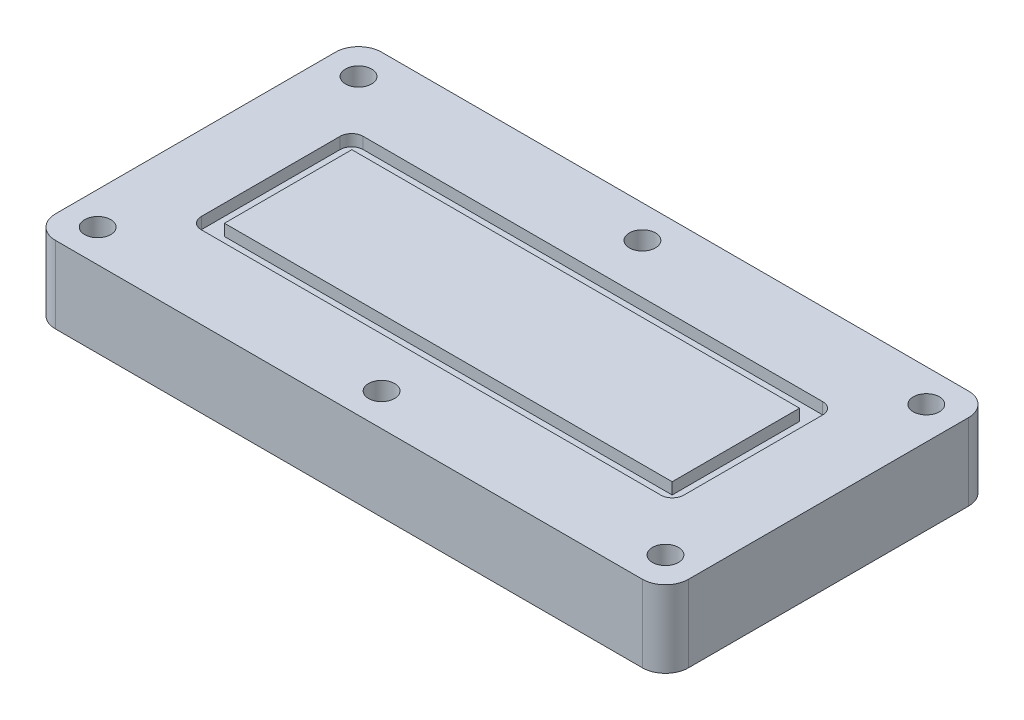
SolidWorks part; units mm, degrees
ref_plane "Front Plane" through (0, 0, 0) normal (0, 0, 1) x (1, 0, 0)
ref_plane "Top Plane" through (0, 0, 0) normal (0, 1, 0) x (1, 0, 0)
ref_plane "Right Plane" through (0, 0, 0) normal (1, 0, 0) x (0, 0, -1)
sketch "Sketch1" plane through (0, 0, 0) normal (0, 1, 0) x (1, 0, 0)
  line L1 (-52.3875, -26.9875) -> (52.3875, -26.9875)
  line L2 (-52.3875, -26.9875) -> (-52.3875, 26.9875)
  line L3 (-52.3875, 26.9875) -> (52.3875, 26.9875)
  line L4 (52.3875, -26.9875) -> (52.3875, 26.9875)
  line L5 (-52.3875, -26.9875) -> (52.3875, 26.9875) construction
  line L6 (-52.3875, 26.9875) -> (52.3875, -26.9875) construction
  point P0 (0, 0)
  dimension "D1" = 104.775
  dimension "D2" = 53.975
extrude "Boss-Extrude1" add sketch "Sketch1" along normal blind 12.7
sketch "Sketch3" plane through (0, 12.7, 0) normal (0, 1, 0) x (1, 0, 0)
  line L1 (-39.9415, -13.3985) -> (39.9415, -13.3985)
  line L2 (-39.9415, -13.3985) -> (-39.9415, 13.3985)
  line L3 (-39.9415, 13.3985) -> (39.9415, 13.3985)
  line L4 (39.9415, -13.3985) -> (39.9415, 13.3985)
  line L5 (-39.9415, -13.3985) -> (39.9415, 13.3985) construction
  line L6 (-39.9415, 13.3985) -> (39.9415, -13.3985) construction
  line L7 (-37.0522, -10.541) -> (37.0523, -10.541)
  line L8 (-37.0522, -10.541) -> (-37.0522, 10.541)
  line L9 (-37.0522, 10.541) -> (37.0523, 10.541)
  line L10 (37.0523, -10.541) -> (37.0523, 10.541)
  line L11 (-37.0522, -10.541) -> (37.0523, 10.541) construction
  line L12 (-37.0522, 10.541) -> (37.0523, -10.541) construction
  point P0 (0, 0)
  point P6 (0, 0)
  dimension "D1" = 26.797
  dimension "D2" = 79.883
  dimension "D3" = 21.082
  dimension "D4" = 74.1045
extrude "Cut-Extrude1" cut sketch "Sketch3" against normal blind 1.905
fillet "Fillet1" radius 1.905 4 edges at (39.9415, 11.7475, 13.3985) (39.9415, 11.7475, -13.3985) (-39.9415, 11.7475, 13.3985) (-39.9415, 11.7475, -13.3985)
sketch "Sketch4" plane through (0, 0, 0) normal (0, -1, 0) x (1, 0, 0)
  line L0 (46.99, 21.59) -> (52.3875, 21.59) construction
  line L1 (-52.3875, -26.9875) -> (-52.3875, 26.9875) construction
  line L3 (52.3875, 26.9875) -> (52.3875, -26.9875) construction
  line L6 (-46.99, 21.59) -> (-52.3875, 21.59) construction
  line L7 (-46.99, 21.59) -> (-46.99, 26.9875) construction
  line L8 (-52.3875, 26.9875) -> (52.3875, 26.9875) construction
  line L9 (-46.99, -21.59) -> (-46.99, -26.9875) construction
  line L11 (52.3875, -26.9875) -> (-52.3875, -26.9875) construction
  line L12 (0, -26.9875) -> (0, 26.9875) construction
  circle A0 centre (-46.99, 21.59) radius 2.159
  circle A1 centre (46.99, 21.59) radius 2.159
  circle A2 centre (-46.99, -21.59) radius 2.159
  circle A3 centre (46.99, -21.59) radius 2.159
  circle A4 centre (0, 21.59) radius 2.159
  circle A5 centre (0, -21.59) radius 2.159
  point P22 (-46.99, -21.59)
  point P27 (0, 0)
  dimension "D3" = 4.318
  dimension "D4" = 4.318
  dimension "D5" = 4.318
  dimension "D6" = 4.318
  dimension "D7" = 4.318
  dimension "D8" = 4.318
  dimension "D1" = 93.98
  dimension "D2" = 43.18
hole_wizard "CBORE for #4 Pan Head Machine Screw1" positions "Sketch5" profile "Sketch6" counterbore size "#4" standard "ANSI Inch"
sketch "Sketch5" plane through (0, 0, 0) normal (0, -1, 0) x (-1, 0, 0)
  point P0 (-46.99, 21.59)
  point P3 (-46.99, -21.59)
  point P6 (46.99, 21.59)
  point P9 (46.99, -21.59)
  point P13 (0, 21.59)
  point P16 (0, -21.59)
sketch "Sketch6" plane through (46.99, 0, -21.59) normal (1, 0, 0) x (0, 0, -1)
  line L0 (0, 0) -> (0, 11.1406)
  line L1 (0, 11.1406) -> (1.6319, 10.16)
  line L2 (1.6319, 10.16) -> (1.6319, 2.032)
  line L3 (1.6319, 2.032) -> (3.175, 2.032)
  line L4 (3.175, 2.032) -> (3.175, 0)
  line L5 (3.175, 0) -> (0, 0)
  line L10 (0, 11.1406) -> (-1.632, 10.16) construction
  line L11 (0, -6.35) -> (0, 107.95) construction
  dimension "Hole Dia." = 3.2639
  dimension "Hole Depth" = 10.16
  dimension "C'Bore Dia." = 6.35
  dimension "C'Bore Depth" = 2.032
  dimension "Drill Angle" = 118
extrude "Cut-Extrude2" cut sketch "Sketch4" against normal through all
sketch "Sketch8" plane through (0, 0, 0) normal (0, -1, 0) x (1, 0, 0)
  circle A0 centre (-46.99, 21.59) radius 3.6195
  circle A1 centre (0, 21.59) radius 3.6195
  circle A2 centre (46.99, 21.59) radius 3.6195
  circle A3 centre (46.99, -21.59) radius 3.6195
  circle A4 centre (0, -21.59) radius 3.6195
  circle A5 centre (-46.99, -21.59) radius 3.6195
  point P5 (0, 21.59)
  point P9 (46.99, 21.59)
  point P13 (46.99, -21.59)
  point P17 (0, -21.59)
  point P21 (0, 0)
  point P22 (-46.99, -21.59)
  dimension "D1" = 7.239
  dimension "D2" = 7.239
  dimension "D3" = 7.239
  dimension "D4" = 7.239
  dimension "D5" = 7.239
  dimension "D6" = 7.239
extrude "Cut-Extrude3" cut sketch "Sketch8" against normal blind 4.572
fillet "Fillet2" radius 3.81 4 edges at (-52.3875, 6.35, 26.9875) (-52.3875, 6.35, -26.9875) (52.3875, 6.35, 26.9875) (52.3875, 6.35, -26.9875)
